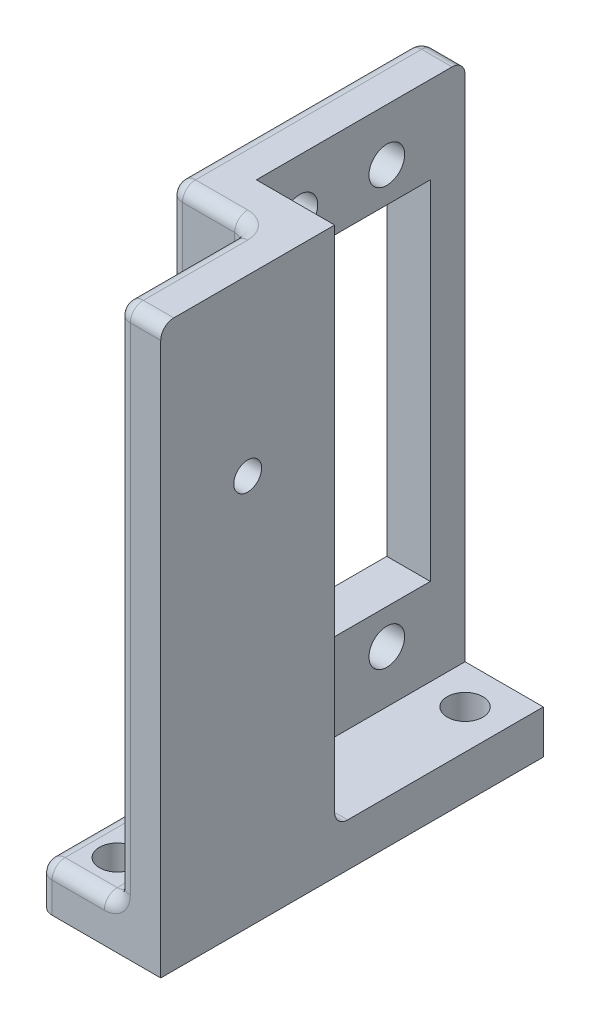
SolidWorks part; units mm, degrees
ref_plane "Plan de face" through (0, 0, 0) normal (0, 0, 1) x (1, 0, 0)
ref_plane "Plan de dessus" through (0, 0, 0) normal (0, 1, 0) x (1, 0, 0)
ref_plane "Plan de droite" through (0, 0, 0) normal (1, 0, 0) x (0, 0, -1)
sketch "Esquisse5" plane through (0, 0, 0) normal (0, 1, 0) x (1, 0, 0)
  line L0 (0, 33.1671) -> (0, -35.3381) construction
  line L1 (-46.3134, 0) -> (70.3268, 0) construction
  line L2 (0, 0) -> (0, 44)
  line L3 (0, 44) -> (14, 44)
  line L4 (14, 44) -> (14, 0)
  line L5 (14, 0) -> (0, 0)
  dimension "D1" = 44
  dimension "D2" = 14
extrude "Boss.-Extru.2" add sketch "Esquisse5" along normal blind 5
sketch "Esquisse6" plane through (0, 5, 0) normal (0, 1, 0) x (1, 0, 0)
  line L0 (9, 0) -> (9, 15)
  line L1 (9, 15) -> (0, 15)
  line L2 (5, 44) -> (5, 20)
  line L3 (5, 20) -> (14, 20)
  line L4 (0, 0) -> (14, 0)
  line L5 (14, 0) -> (14, 44)
  line L6 (14, 44) -> (0, 44)
  line L7 (0, 44) -> (0, 0)
  line L8 (0, 0) -> (14, 0)
  line L9 (14, 0) -> (14, 44)
  line L10 (14, 44) -> (0, 44)
  line L11 (0, 44) -> (0, 0)
  line M9 (0, 0) -> (14, 0)
  line M10 (14, 0) -> (14, 44)
  line M11 (14, 44) -> (0, 44)
  line M12 (0, 44) -> (0, 0)
  dimension "D2" = 5
  dimension "D3" = 24
  dimension "D4" = 5
  dimension "D5" = 5
  dimension "D1" = 0
extrude "Boss.-Extru.3" add sketch "Esquisse6" along normal blind 60 contours L3 L2 L1 L0 M11 M12 M9 M10
sketch "Esquisse8" plane through (0, 0, 0) normal (1, 0, 0) x (0, 0, -1)
  line L0 (0, 35.7163) -> (0, 0) construction
  line L1 (0, 0) -> (41.4374, 0) construction
  line L2 (20, 35) -> (-36.5895, 35) construction
  line L3 (15, 5) -> (44, 5) construction
  line L4 (44, 65) -> (44, 0) construction
  line L5 (-15, 0) -> (24.1506, 39.1506) construction
  line L6 (55, 0) -> (-8.5486, 63.5486) construction
  line L7 (20, 25) -> (20, 32.2252) construction
  circle A0 centre (30, 25) radius 1.6
  circle A1 centre (30, 25) radius 10 construction
  circle A6 centre (10, 45) radius 10 construction
  circle A7 centre (10, 45) radius 1.6
  dimension "D4" = 3.2
  dimension "D5" = 20
  dimension "D6" = 35
  dimension "D1" = 20
  dimension "D2" = 45
  dimension "D3" = 45
extrude "Enlèv. mat.-Extru.2" cut sketch "Esquisse8" against normal through all and the other way through all contours A0 | A7
sketch "Esquisse10" plane through (0, 0, 0) normal (-1, 0, 0) x (0, 0, 1)
  line L0 (-30, 62.1315) -> (-30, 10.1433) construction
  line L1 (-28.7451, 11) -> (-18.6924, 11) construction
  line L3 (-49.7511, 35) -> (-17.4847, 35) construction
  line L5 (-20, 55) -> (-40, 55)
  line L6 (-44, 0) -> (0, 0)
  line L7 (0, 0) -> (0, 5)
  line L8 (0, 5) -> (-15, 5)
  line L9 (-15, 5) -> (-15, 65)
  line L10 (-15, 65) -> (-44, 65)
  line L11 (-44, 65) -> (-44, 0)
  line L12 (-44, 0) -> (0, 0)
  line L13 (0, 0) -> (0, 5)
  line L14 (0, 5) -> (-15, 5)
  line L15 (-15, 5) -> (-15, 65)
  line L16 (-15, 65) -> (-44, 65)
  line L17 (-44, 65) -> (-44, 0)
  line L18 (-20, 55) -> (-20, 15)
  line L19 (-20, 15) -> (-40, 15)
  line L20 (-40, 55) -> (-40, 15)
  line L21 (-20, 55) -> (-40, 15) construction
  line L22 (-20, 15) -> (-40, 55) construction
  circle A0 centre (-30, 25) radius 1.6 construction
  circle A1 centre (-30, 25) radius 1.6
  circle A2 centre (-35, 11) radius 2.05
  circle A3 centre (-25, 11) radius 2.05
  circle A4 centre (-35, 59) radius 2.05
  circle A5 centre (-25, 59) radius 2.05
  point P19 (-30, 35)
  circle M7 centre (-30, 25) radius 1.6
  dimension "D2" = 10
  dimension "D3" = 4.1
  dimension "D4" = 5
  dimension "D5" = 20
  dimension "D6" = 40
  dimension "D7" = 4
  dimension "D1" = 0
extrude "Enlèv. mat.-Extru.3" cut sketch "Esquisse10" against normal through all contours A3 | A2 | L5 L20 L19 L18 M7 | A5 | A4
sketch "Esquisse11" plane through (0, 5, 0) normal (0, 1, 0) x (1, 0, 0)
  line L4 (0, 0) -> (9, 0)
  line L5 (9, 0) -> (9, 15)
  line L6 (9, 15) -> (0, 15)
  line L7 (0, 15) -> (0, 0)
  line L8 (0, 0) -> (9, 0)
  line L9 (9, 0) -> (9, 15)
  line L10 (9, 15) -> (0, 15)
  line L11 (0, 15) -> (0, 0)
  line L12 (5, 44) -> (5, 20)
  line L13 (5, 20) -> (14, 20)
  line L14 (14, 20) -> (14, 44)
  line L15 (14, 44) -> (5, 44)
  line L16 (5, 44) -> (5, 20)
  line L17 (5, 20) -> (14, 20)
  line L18 (14, 20) -> (14, 44)
  line L19 (14, 44) -> (5, 44)
  circle A0 centre (9.5, 39.5) radius 2.05
  circle A1 centre (4.5, 4.5) radius 2.05
  dimension "D3" = 4.1
  dimension "D4" = 4.5
  dimension "D5" = 4.5
  dimension "D6" = 4.5
  dimension "D7" = 4.5
  dimension "D1" = 0
  dimension "D2" = 0
extrude "Enlèv. mat.-Extru.4" cut sketch "Esquisse11" against normal through all contours A0 | A1
fillet "Congé3" radius 1.5 15 edges at (9, 65, -7.5) (9, 35, -15) (9.5, 5, -20) (9, 5, -7.5) (4.5, 5, -15) (2.5, 65, -44) (4.5, 65, -15) (11.5, 65, 0) (0, 2.5, 0) (0, 32.5, -44) (0, 35, -15) (9, 35, 0) (4.5, 5, 0) (0, 65, -29.5) (0, 5, -7.5)
